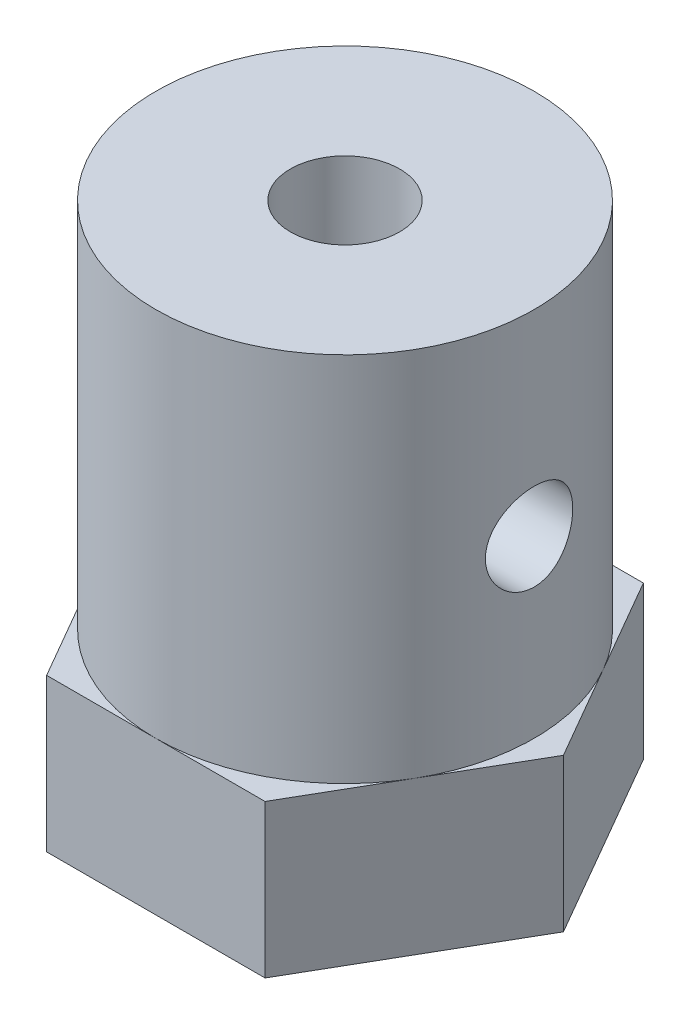
SolidWorks part; units mm, degrees
ref_plane "前视基准面" through (0, 0, 0) normal (0, 0, 1) x (1, 0, 0)
ref_plane "上视基准面" through (0, 0, 0) normal (0, 1, 0) x (1, 0, 0)
ref_plane "右视基准面" through (0, 0, 0) normal (1, 0, 0) x (0, 0, -1)
sketch "草图1" plane through (0, 0, 0) normal (0, 1, 0) x (1, 0, 0)
  line L6 (10, 0) -> (5, 8.6603)
  line L7 (-5, 8.6603) -> (5, 8.6603)
  line L8 (-5, 8.6603) -> (-10, 0)
  line L9 (-5, -8.6603) -> (-10, 0)
  line L10 (-5, -8.6603) -> (5, -8.6603)
  line L11 (10, 0) -> (5, -8.6603)
extrude "凸台-拉伸1" add sketch "草图1" along normal blind 7 contours L10 L11 L6 L7 L8 L9
sketch "草图2" plane through (0, 0, 0) normal (0, -1, 0) x (1, 0, 0)
  circle A0 centre (0, 0) radius 2
  circle A2 centre (-5, 2.8868) radius 2
  circle A3 centre (5, 2.8868) radius 2
  circle A4 centre (0, -5.7735) radius 2
sketch "草图5" plane through (0, 7, 0) normal (0, 1, 0) x (1, 0, 0)
  circle A0 centre (0, 0) radius 2.5
  circle A1 centre (0, 0) radius 8.6603
extrude "凸台-拉伸2" add sketch "草图5" along normal blind 17
extrude "切除-拉伸4" cut sketch "草图2" against normal blind 7
sketch "草图6" plane through (0, 0, 0) normal (1, 0, 0) x (0, 0, -1)
  line L2 (0, 0) -> (0, 15)
  circle A0 centre (0, 15) radius 2
extrude "切除-拉伸5" cut sketch "草图6" against normal through all both and the other way through all contours A0
